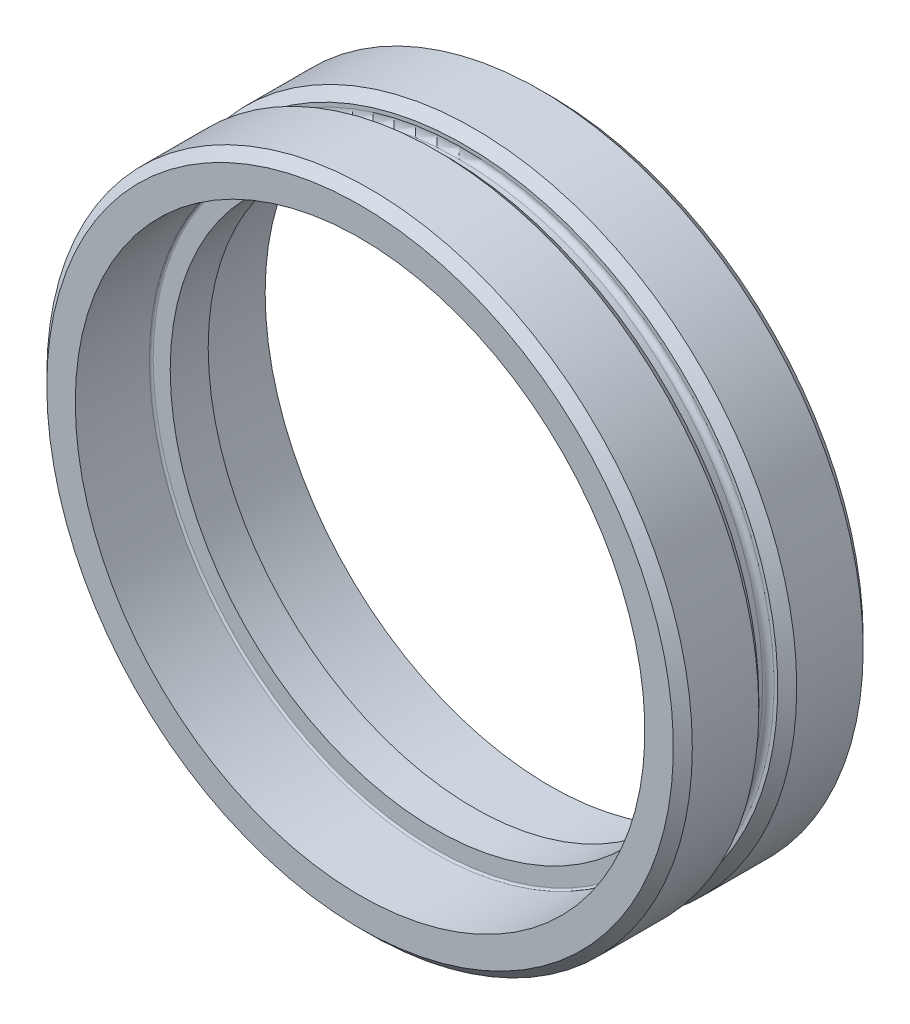
SolidWorks part; units mm, degrees
material "ABS"
ref_plane "Спереди" through (0, 0, 0) normal (0, 0, 1) x (1, 0, 0)
ref_plane "Сверху" through (0, 0, 0) normal (0, 1, 0) x (1, 0, 0)
ref_plane "Справа" through (0, 0, 0) normal (1, 0, 0) x (0, 0, -1)
sketch "Эскиз18" plane through (0, 0, 0) normal (1, 0, 0) x (0, 0, -1)
  line L0 (0, 0) -> (-13.7701, 0) construction
  line L2 (-10, -15) -> (-6, -15)
  line L3 (-6, -15) -> (-6, -14)
  line L4 (-6, -14) -> (-4, -14)
  line L5 (-4, -14) -> (-4, -15)
  line L6 (-4, -15) -> (0, -15)
  line L7 (-10, -17) -> (-10, -15)
  line L13 (0, -17) -> (0, -15)
  line L14 (-5, -14) -> (-5, -18.1745) construction
  line L15 (0, -17) -> (-4.5, -17)
  line L16 (-4.5, -17) -> (-4.5, -16)
  line L17 (-4.5, -16) -> (-5.5, -16)
  line L18 (-5.5, -16) -> (-5.5, -17)
  line L19 (-5.5, -17) -> (-10, -17)
  dimension "D1" = 34
  dimension "D2" = 30
  dimension "D3" = 4
  dimension "D4" = 10
  dimension "D5" = 4
  dimension "D6" = 1
  dimension "D7" = 1
  dimension "D9" = 1
revolve "Повернуть1" add sketch "Эскиз18" angle 360 about L0
fillet "Скругление1" radius 0.3 2 edges at (-16, 0, 4.5) (-16, 0, 5.5)
chamfer "Фаска1" distance 0.5 angle 45 4 edges at (-17, 0, 4.5) (-17, 0, 0) (-17, 0, 10) (-17, 0, 5.5)
fillet "Скругление2" radius 0.1 2 edges at (-15, 0, 6) (-15, 0, 4)
